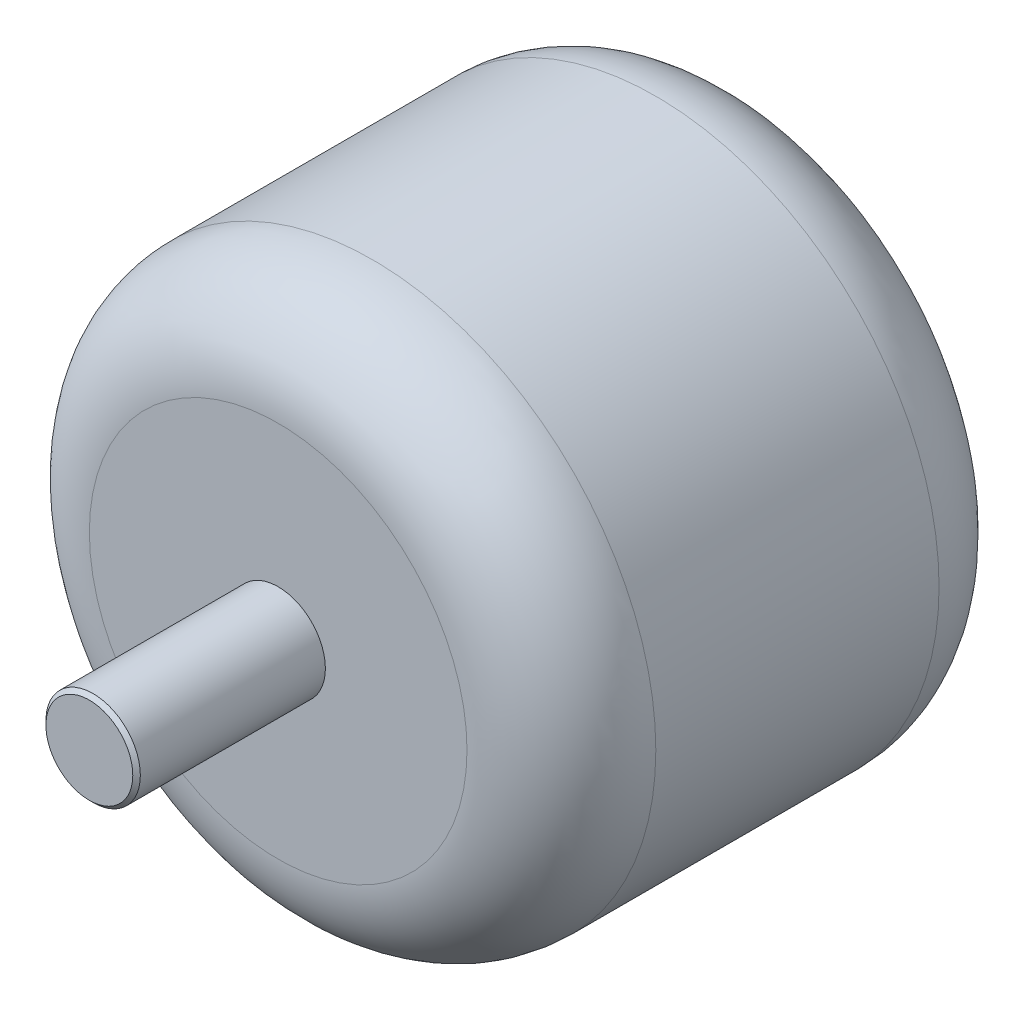
SolidWorks part; units mm, degrees
ref_plane "Front Plane" through (0, 0, 0) normal (0, 0, 1) x (1, 0, 0)
ref_plane "Top Plane" through (0, 0, 0) normal (0, 1, 0) x (1, 0, 0)
ref_plane "Right Plane" through (0, 0, 0) normal (1, 0, 0) x (0, 0, -1)
sketch "Sketch1" plane through (0, 0, 0) normal (0, 0, 1) x (1, 0, 0)
  circle A0 centre (0, 0) radius 15
  dimension "D1" = 30
extrude "Boss-Extrude1" add sketch "Sketch1" along normal blind 15 and the other way blind 10
fillet "Fillet1" radius 5 2 edges at (15, 0, -10) (15, 0, 15)
sketch "Sketch2" plane through (0, 0, 15) normal (0, 0, 1) x (1, 0, 0)
  circle A0 centre (0, 0) radius 2.5
  dimension "D1" = 5
extrude "Boss-Extrude2" add sketch "Sketch2" along normal blind 10
chamfer "Chamfer1" distance 0.2 angle 45 1 edges at (2.5, 0, 25)
sketch "Sketch3" plane through (0, 0, -10) normal (0, 0, -1) x (-1, 0, 0)
  line L0 (0, 6) -> (0, 0) construction
  circle A0 centre (0, 6) radius 1
  dimension "D1" = 2
  dimension "D2" = 6
extrude "Cut-Extrude1" cut sketch "Sketch3" against normal blind 3
pattern_circular "CirPattern1" count 3 over 360 about axis through (0, 0, 0) along (0, 0, 1) of "Cut-Extrude1"
